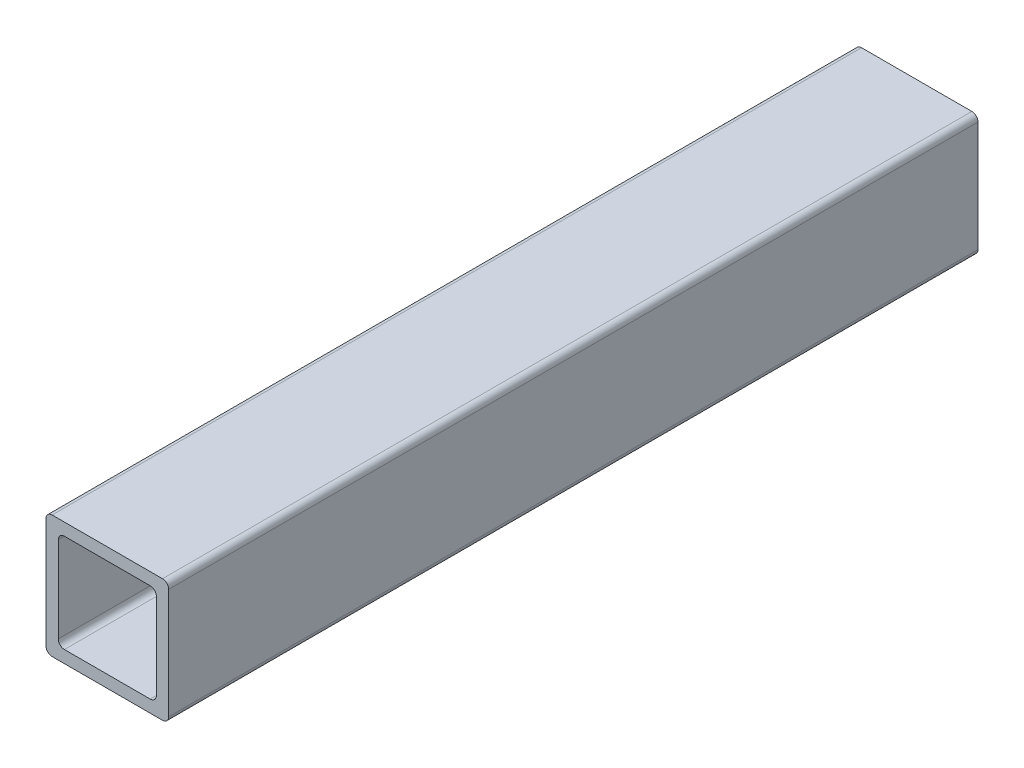
SolidWorks part; units mm, degrees
ref_plane "Plan de face" through (0, 0, 0) normal (0, 0, 1) x (1, 0, 0)
ref_plane "Plan de dessus" through (0, 0, 0) normal (0, 1, 0) x (1, 0, 0)
ref_plane "Plan de droite" through (0, 0, 0) normal (1, 0, 0) x (0, 0, -1)
sketch "Esquisse2" plane through (0, 0, 0) normal (0, 0, 1) x (1, 0, 0)
  line L0 (6, 4) -> (34, 4)
  line L1 (2, 0) -> (38, 0)
  line L2 (0, 2) -> (0, 38)
  line L3 (2, 40) -> (38, 40)
  line L4 (40, 2) -> (40, 38)
  line L5 (36, 6) -> (36, 34)
  line L6 (6, 36) -> (34, 36)
  line L7 (4, 6) -> (4, 34)
  line L8 (4, 4) -> (36, 4) construction
  line L9 (36, 4) -> (36, 36) construction
  line L10 (4, 36) -> (36, 36) construction
  line L11 (4, 4) -> (4, 36) construction
  line L12 (0, 0) -> (40, 0) construction
  line L13 (0, 0) -> (0, 40) construction
  line L14 (0, 40) -> (40, 40) construction
  line L15 (40, 0) -> (40, 40) construction
  arc A0 (34, 4) -> (36, 6) centre (34, 6) ccw
  arc A1 (36, 34) -> (34, 36) centre (34, 34) ccw
  arc A2 (6, 36) -> (4, 34) centre (6, 34) ccw
  arc A3 (4, 6) -> (6, 4) centre (6, 6) ccw
  arc A4 (2, 0) -> (0, 2) centre (2, 2) cw
  arc A5 (0, 38) -> (2, 40) centre (2, 38) cw
  arc A6 (38, 40) -> (40, 38) centre (38, 38) cw
  arc A7 (40, 2) -> (38, 0) centre (38, 2) cw
  point P24 (0, 0)
  dimension "D4" = 2
  dimension "D1" = 40
  dimension "D2" = 40
  dimension "D3" = 4
extrude "Boss.-Extru.1" add sketch "Esquisse2" along normal blind 264
